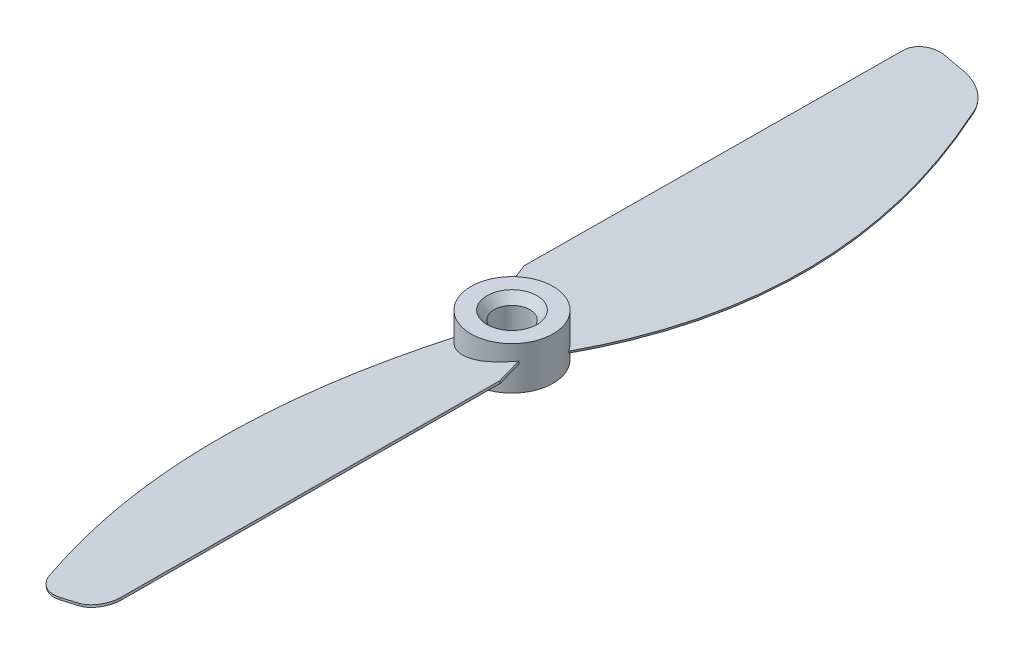
SolidWorks part; units mm, degrees
ref_plane "Front Plane" through (0, 0, 0) normal (0, 0, 1) x (1, 0, 0)
ref_plane "Top Plane" through (0, 0, 0) normal (0, 1, 0) x (1, 0, 0)
ref_plane "Right Plane" through (0, 0, 0) normal (1, 0, 0) x (0, 0, -1)
sketch "Sketch1" plane through (0, 0, 0) normal (0, 1, 0) x (1, 0, 0)
  circle A0 centre (0, 0) radius 5.75
  dimension "D1" = 11.5
extrude "Boss-Extrude1" add sketch "Sketch1" along normal mid plane 6
sketch "Sketch2" plane through (0, 0, 0) normal (0, 0, 1) x (1, 0, 0)
  line L0 (-5.75, 1.3275) -> (5.75, -1.3275) construction
  line L1 (-5.75, 3) -> (-5.75, -3) construction
  line L2 (5.75, -3) -> (5.75, 3) construction
  line L3 (-5.75, -3) -> (5.75, -3) construction
  point P6 (0, 0)
  dimension "D1" = 13
ref_plane "Plane1" through (0, 0, 0) normal (-0.225, -0.9744, 0) x (0.9744, -0.225, 0)
sketch "Sketch3" plane through (0, 0, 0) normal (-0.225, -0.9744, 0) x (0.9744, -0.225, 0)
  line L0 (-4.8698, -3.8114) -> (-6.2775, -7.8114)
  line L1 (-6.2775, -7.8114) -> (-5.9308, -60.5197)
  line L2 (-2.9309, -63.5) -> (-0.266, -63.5)
  arc A0 (-5.9308, -60.5197) -> (-2.9309, -63.5) centre (-2.9309, -60.5) ccw
  arc A1 (4.5159, -59.9606) -> (-0.266, -63.5) centre (-0.266, -58.5) cw
  ellipse E0 centre (-0.6749, 0) end of major axis (-0.6749, 5.75) minor radius 5.6026 construction
  spline S0 degree 2 poles (-4.8698, -3.8114) (0.6345, -8.0396) (4.5159, -2.0647) knots 0 0 0 1 1 1
  spline S1 degree 2 poles (4.5159, -59.9606) (16.6278, -30.5037) (4.5159, -2.0647) knots 0 0 0 1 1 1
  dimension "D3" = 3
  dimension "D4" = 5
  dimension "D1" = 63.5
  dimension "D2" = 4
extrude "Boss-Extrude3" add sketch "Sketch3" along normal blind 0.3
pattern_circular "CirPattern1" count 2 over 360 about axis through (0, 3, 0) along (0, -1, 0) of "Boss-Extrude3"
sketch "Sketch4" plane through (0, 3, 0) normal (0, 1, 0) x (1, 0, 0)
  circle A0 centre (0, 0) radius 2.5
  dimension "D1" = 5
extrude "Cut-Extrude1" cut sketch "Sketch4" against normal through all
chamfer "Chamfer1" distance 1 angle 50 2 edges at (0, 3, 2.5) (0, -3, 2.5)
